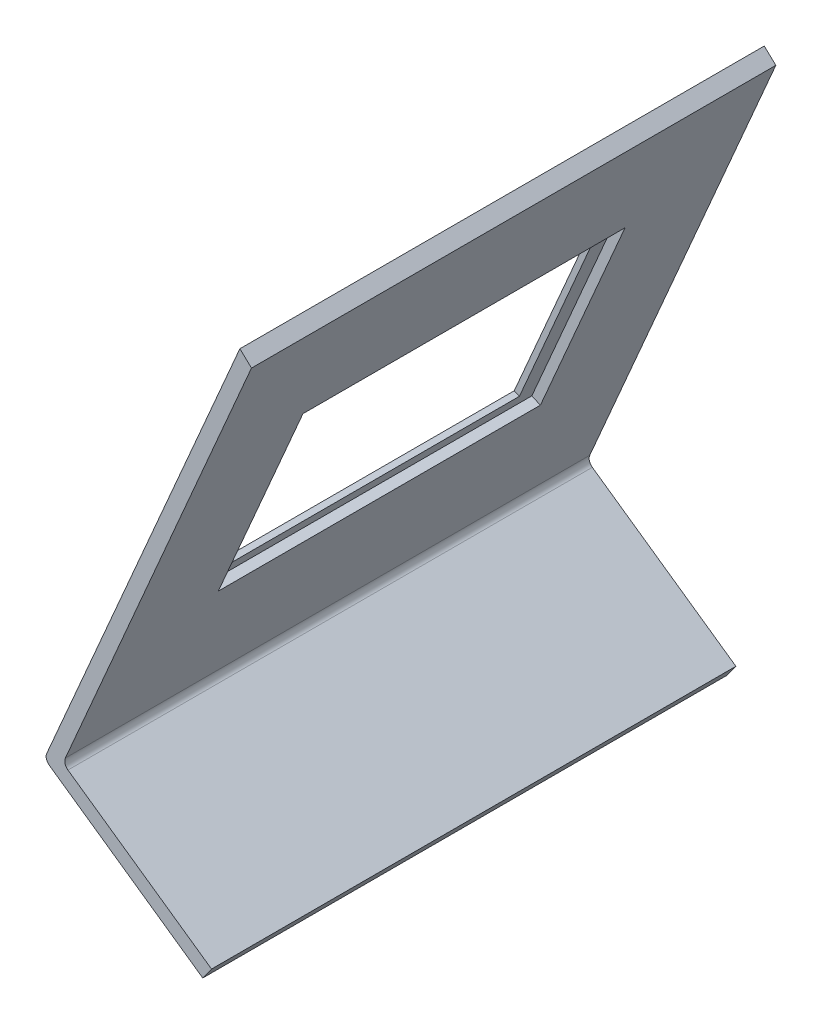
SolidWorks part; units mm, degrees
ref_plane "Plano frontal" through (0, 0, 0) normal (0, 0, 1) x (1, 0, 0)
ref_plane "Plano superior" through (0, 0, 0) normal (0, 1, 0) x (1, 0, 0)
ref_plane "Plano direito" through (0, 0, 0) normal (1, 0, 0) x (0, 0, -1)
sketch "Esboço1" plane through (0, 0, 0) normal (0, 0, 1) x (1, 0, 0)
  line L0 (-183.8867, 0) -> (223.7337, 0) construction
  line L2 (-41.6464, 31.1103) -> (9.9099, 150.4499)
  line L3 (9.9099, 150.4499) -> (13.5818, 148.8636)
  line L4 (13.5818, 148.8636) -> (-36.6815, 32.5169)
  line L6 (0, 0) -> (2.3428, 3.2427)
  line L7 (13.5818, 148.8636) -> (13.5818, 0) construction
  line L8 (-40.9576, 28.6788) -> (0, 0)
  line L9 (-35.9926, 30.0854) -> (2.3428, 3.2427)
  arc A0 (-36.6815, 32.5169) -> (-35.9926, 30.0854) centre (-34.8455, 31.7237) ccw
  arc A1 (-40.9576, 28.6788) -> (-41.6464, 31.1103) centre (-39.8104, 30.3171) cw
  dimension "D1" = 35
  dimension "D2" = 2
  dimension "D7" = 54.153
  dimension "D3" = 130
  dimension "D4" = 4
  dimension "D5" = 4
  dimension "D6" = 50
  dimension "D8" = 13.5818
extrude "Ressalto-extrusão1" add sketch "Esboço1" against normal blind 140
sketch "Esboço3" plane through (-42.7504, 18.4688, 0) normal (0.918, -0.3966, 0) x (0, 0, -1)
  line L0 (31.5, 104.1729) -> (108.5, 104.1729)
  line L1 (108.5, 104.1729) -> (108.5, 53.1729)
  line L2 (108.5, 53.1729) -> (31.5, 53.1729)
  line L3 (31.5, 53.1729) -> (31.5, 104.1729)
  line L4 (31.5, 104.1729) -> (108.5, 53.1729) construction
  line L5 (0, 142.0427) -> (140, 15.303) construction
  line L6 (27, 107.1729) -> (113, 107.1729)
  line L7 (113, 107.1729) -> (113, 50.1729)
  line L8 (113, 50.1729) -> (27, 50.1729)
  line L9 (27, 50.1729) -> (27, 107.1729)
  line L10 (27, 107.1729) -> (113, 50.1729) construction
  point P8 (70, 78.6729)
  point P9 (70, 78.6729)
  point P10 (70, 78.6729)
  dimension "D1" = 77
  dimension "D2" = 51
  dimension "D3" = 86
  dimension "D4" = 57
extrude "Corte-extrusão1" cut sketch "Esboço3" against normal blind 2.5
sketch "Esboço4" plane through (-42.7504, 18.4688, 0) normal (0.918, -0.3966, 0) x (0, 0, -1)
  line L0 (31.5, 104.1729) -> (31.5, 53.1729)
  line L1 (31.5, 53.1729) -> (108.5, 53.1729)
  line L2 (108.5, 53.1729) -> (108.5, 104.1729)
  line L3 (108.5, 104.1729) -> (31.5, 104.1729)
extrude "Corte-extrusão2" cut sketch "Esboço4" against normal through all
sketch "Esboço5" plane through (0, 0, 0) normal (0, 0, 1) x (1, 0, 0)
  line L0 (9.9099, 150.4499) -> (13.0045, 147.5271)
  line L1 (-36.6815, 32.5169) -> (13.5818, 148.8636) construction
  line L2 (13.0045, 147.5271) -> (13.5818, 148.8636)
  line L3 (13.5818, 148.8636) -> (9.9099, 150.4499) construction
  line L4 (13.5818, 148.8636) -> (9.9099, 150.4499)
  line L5 (3.3601, 150.4499) -> (21.4426, 150.4499) construction
  line L6 (-18.9452, 0) -> (16.8885, 0) construction
  line L7 (13.0045, 147.5271) -> (13.0045, 0) construction
  dimension "D1" = 20
extrude "Corte-extrusão3" cut sketch "Esboço5" against normal through all
